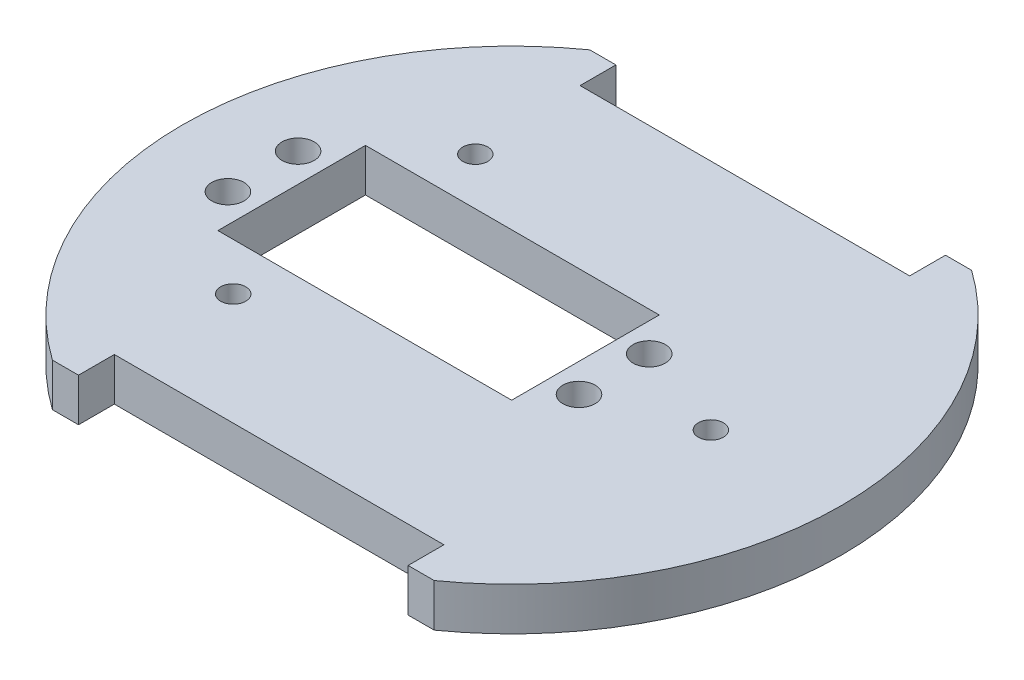
SolidWorks part; units mm, degrees
ref_plane "Front Plane" through (0, 0, 0) normal (0, 0, 1) x (1, 0, 0)
ref_plane "Top Plane" through (0, 0, 0) normal (0, 1, 0) x (1, 0, 0)
ref_plane "Right Plane" through (0, 0, 0) normal (1, 0, 0) x (0, 0, -1)
sketch "Sketch1" plane through (0, 0, 0) normal (0, 1, 0) x (1, 0, 0)
  line L0 (-26.6411, 37.5) -> (-23, 37.5)
  line L1 (-23, 32.5) -> (23, 32.5)
  line L2 (-23, 32.5) -> (-23, 37.5)
  line L3 (23, 32.5) -> (23, 37.5)
  line L4 (23, 37.5) -> (26.6411, 37.5)
  line L5 (0, 0) -> (-46, 0) construction
  line L6 (23, -37.5) -> (26.6411, -37.5)
  line L7 (23, -32.5) -> (23, -37.5)
  line L8 (-26.6411, -37.5) -> (-23, -37.5)
  line L9 (-23, -32.5) -> (-23, -37.5)
  line L10 (-23, -32.5) -> (23, -32.5)
  line L11 (27.75, 0) -> (-21.93, 0) construction
  line L12 (-30.75, -10.3) -> (10.25, -10.3)
  line L13 (-30.75, -10.3) -> (-30.75, 10.3)
  line L14 (-30.75, 10.3) -> (10.25, 10.3)
  line L15 (10.25, -10.3) -> (10.25, 10.3)
  line L16 (-30.75, -10.3) -> (10.25, 10.3) construction
  line L17 (-30.75, 10.3) -> (10.25, -10.3) construction
  line L18 (-21.93, 17) -> (-21.93, -17) construction
  line L19 (14.25, 4.9) -> (14.25, -4.9) construction
  line L20 (-10.25, 0) -> (-10.25, -10.3) construction
  line L24 (-22.0156, -16.8931) -> (0, 0) construction
  line L25 (-22.0156, 16.8931) -> (0, 0) construction
  line L26 (-22.0156, 16.8931) -> (-22.0156, -16.8931) construction
  arc A0 (-26.6411, 37.5) -> (-26.6411, -37.5) centre (0, 0) ccw
  arc A1 (26.6411, -37.5) -> (26.6411, 37.5) centre (0, 0) ccw
  circle A7 centre (14.25, 4.9) radius 2.25
  circle A8 centre (14.25, -4.9) radius 2.25
  circle A9 centre (-34.75, 4.9) radius 2.25
  circle A10 centre (-34.75, -4.9) radius 2.25
  circle A11 centre (27.75, 0) radius 1.75
  circle A12 centre (-22.0156, 16.8931) radius 1.75
  circle A13 centre (-22.0156, -16.8931) radius 1.75
  point P8 (0, 32.5)
  point P16 (-10.25, 0)
  point P21 (10.25, 0)
  point P26 (-30.75, 0)
  point P33 (14.25, 0)
  dimension "D1" = 92
  dimension "D8" = 9.8
  dimension "D10" = 4.5
  dimension "D15" = 27.75
  dimension "D16" = 27.75
  dimension "D11" = 3.5
  dimension "D18" = 3.5
  dimension "D19" = 3.5
  dimension "D2" = 37.5
  dimension "D3" = 46
  dimension "D4" = 5
  dimension "D5" = 41
  dimension "D6" = 20.6
  dimension "D7" = 10.25
  dimension "D9" = 4
  dimension "D12" = 34
  dimension "D13" = 27.75
  dimension "D14" = 49.68
  dimension "D17" = 75
extrude "Boss-Extrude1" add sketch "Sketch1" along normal blind 6
sketch "Sketch2" plane through (0, 6, 0) normal (0, 1, 0) x (1, 0, 0)
  line L0 (-30.75, 0) -> (0, 0) construction
  line L5 (23, 32.5) -> (-23, 32.5) construction
  line L6 (-16.5, 25) -> (-12.5, 25)
  line L7 (-16.5, 25) -> (-16.5, 32.5)
  line L8 (-18.25, 25) -> (-10.75, 25)
  line L9 (-18.25, 25) -> (-18.25, 21)
  line L10 (-18.25, 21) -> (-10.75, 21)
  line L11 (-10.75, 25) -> (-10.75, 21)
  line L12 (-18.25, 25) -> (-10.75, 21) construction
  line L13 (-18.25, 21) -> (-10.75, 25) construction
  line L14 (-16.5, 32.5) -> (-12.5, 32.5)
  line L15 (-12.5, 25) -> (-12.5, 32.5)
  line L16 (-16.5, 25) -> (-12.5, 32.5) construction
  line L17 (-16.5, 32.5) -> (-12.5, 25) construction
  line L18 (-30.75, 10.3) -> (-30.75, -10.3) construction
  line L19 (0, -32.5) -> (0, 32.5) construction
  line L20 (16.5, 32.5) -> (12.5, 25) construction
  line L21 (16.5, 25) -> (12.5, 32.5) construction
  line L22 (12.5, 25) -> (12.5, 32.5)
  line L23 (16.5, 25) -> (16.5, 32.5)
  line L24 (18.25, 21) -> (10.75, 25) construction
  line L25 (18.25, 25) -> (10.75, 21) construction
  line L26 (10.75, 25) -> (10.75, 21)
  line L27 (18.25, 21) -> (10.75, 21)
  line L28 (18.25, 25) -> (18.25, 21)
  line L29 (18.25, 25) -> (10.75, 25)
  line L30 (16.5, 25) -> (12.5, 25)
  line L31 (18.25, -25) -> (10.75, -21) construction
  line L32 (18.25, -21) -> (10.75, -25) construction
  line L33 (16.5, -25) -> (12.5, -32.5) construction
  line L34 (16.5, -32.5) -> (12.5, -25) construction
  line L35 (-16.5, -32.5) -> (-12.5, -25) construction
  line L36 (-16.5, -25) -> (-12.5, -32.5) construction
  line L37 (-18.25, -21) -> (-10.75, -25) construction
  line L38 (-18.25, -25) -> (-10.75, -21) construction
  line L39 (16.5, -25) -> (12.5, -25)
  line L40 (18.25, -25) -> (10.75, -25)
  line L41 (18.25, -25) -> (18.25, -21)
  line L42 (10.75, -25) -> (10.75, -21)
  line L43 (16.5, -25) -> (16.5, -32.5)
  line L44 (12.5, -25) -> (12.5, -32.5)
  line L45 (-12.5, -25) -> (-12.5, -32.5)
  line L46 (-10.75, -25) -> (-10.75, -21)
  line L47 (-18.25, -25) -> (-18.25, -21)
  line L48 (-18.25, -25) -> (-10.75, -25)
  line L49 (-16.5, -25) -> (-16.5, -32.5)
  line L50 (-16.5, -25) -> (-12.5, -25)
  line L51 (18.25, -21) -> (10.75, -21)
  line L52 (-18.25, -21) -> (-10.75, -21)
  point P0 (-14.5, 28.75)
  point P7 (-14.5, 23)
  point P23 (14.5, 28.75)
  point P28 (14.5, 23)
  point P46 (14.5, -23)
  point P47 (14.5, -28.75)
  point P48 (-14.5, -23)
  point P49 (-14.5, -28.75)
  dimension "D1" = 6.5
  dimension "D2" = 4
  dimension "D3" = 7.5
  dimension "D4" = 4
  dimension "D5" = 7.5
